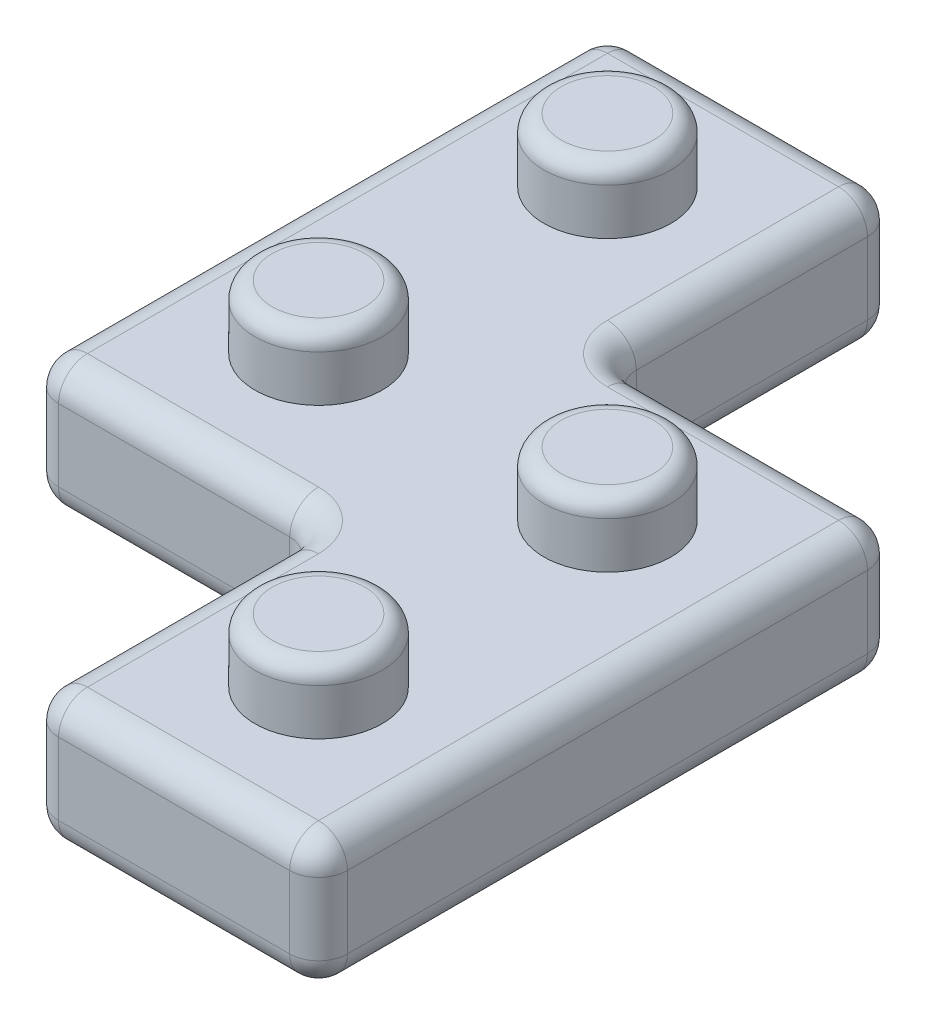
SolidWorks part; units mm, degrees
ref_plane "Front Plane" through (0, 0, 0) normal (0, 0, 1) x (1, 0, 0)
ref_plane "Top Plane" through (0, 0, 0) normal (0, 1, 0) x (1, 0, 0)
ref_plane "Right Plane" through (0, 0, 0) normal (1, 0, 0) x (0, 0, -1)
sketch "Sketch1" plane through (0, 0, 0) normal (0, 1, 0) x (1, 0, 0)
  line L0 (-11.43, 12.7) -> (-1.27, 12.7)
  line L1 (0, 11.43) -> (0, 1.27)
  line L2 (1.27, 0) -> (11.43, 0)
  line L3 (12.7, -1.27) -> (12.7, -24.13)
  line L4 (11.43, -25.4) -> (1.27, -25.4)
  line L5 (0, -24.13) -> (0, -13.97)
  line L6 (-1.27, -12.7) -> (-11.43, -12.7)
  line L7 (-12.7, -11.43) -> (-12.7, 11.43)
  arc A4 (-11.43, 12.7) -> (-12.7, 11.43) centre (-11.43, 11.43) ccw
  arc A5 (-11.43, -12.7) -> (-12.7, -11.43) centre (-11.43, -11.43) cw
  arc A6 (0, -13.97) -> (-1.27, -12.7) centre (-1.27, -13.97) ccw
  arc A7 (1.27, -25.4) -> (0, -24.13) centre (1.27, -24.13) cw
  arc A8 (12.7, -24.13) -> (11.43, -25.4) centre (11.43, -24.13) cw
  arc A9 (0, 1.27) -> (1.27, 0) centre (1.27, 1.27) ccw
  arc A10 (11.43, 0) -> (12.7, -1.27) centre (11.43, -1.27) cw
  arc A11 (-1.27, 12.7) -> (0, 11.43) centre (-1.27, 11.43) cw
  point P11 (-12.7, 12.7)
  point P14 (-12.7, -12.7)
  point P17 (0, 0)
  point P18 (0, 0)
  point P19 (0, 0)
  point P22 (0, -25.4)
  point P25 (12.7, -25.4)
  point P28 (0, 0)
  point P31 (12.7, 0)
  point P34 (0, 12.7)
  dimension "D6" = 1.27
  dimension "D1" = 12.7
  dimension "D2" = 12.7
  dimension "D3" = 25.4
  dimension "D4" = 12.7
  dimension "D5" = 25.4
extrude "Boss-Extrude1" add sketch "Sketch1" against normal blind 5.715 contours L7 A4 L0 A11 L1 A9 L2 A10 L3 A8 L4 A7 L5 A6 L6 A5
sketch "Sketch2" plane through (0, 0, 0) normal (0, 1, 0) x (1, 0, 0)
  line L0 (-11.43, 12.7) -> (-1.27, 12.7) construction
  line L1 (-12.7, -11.43) -> (-12.7, 11.43) construction
  circle A0 centre (-6.35, 6.35) radius 2.794
  circle A1 centre (-6.35, -6.35) radius 2.794
  circle A2 centre (6.35, -6.35) radius 2.794
  circle A3 centre (6.35, -19.05) radius 2.794
  point P8 (0, 0)
  point P9 (0, 0)
  point P10 (0, 0)
  dimension "D1" = 12.7
  dimension "D2" = 6.35
  dimension "D3" = 6.35
  dimension "D4" = 12.7
  dimension "D5" = 12.7
extrude "Boss-Extrude2" add sketch "Sketch2" along normal blind 2.794
fillet "Fillet4" radius 1.27 16 edges at (-6.35, 0, 12.7) (0, 0, 19.05) (6.35, 0, 25.4) (12.7, 0, 12.7) (6.35, 0, 0) (0, 0, -6.35) (-6.35, 0, -12.7) (-12.7, 0, 0) (-12.328, 0, 12.328) (-0.372, 0, 13.072) (0.372, 0, 25.028) (12.328, 0, 25.028) (12.328, 0, 0.372) (0.372, 0, -0.372) (-0.372, 0, -12.328) (-12.328, 0, -12.328)
fillet "Fillet5" radius 1.27 16 edges at (0, -5.715, -6.35) (6.35, -5.715, 0) (12.7, -5.715, 12.7) (6.35, -5.715, 25.4) (0, -5.715, 19.05) (-6.35, -5.715, 12.7) (-12.7, -5.715, 0) (-6.35, -5.715, -12.7) (-12.328, -5.715, -12.328) (-12.328, -5.715, 12.328) (-0.372, -5.715, 13.072) (0.372, -5.715, 25.028) (12.328, -5.715, 25.028) (12.328, -5.715, 0.372) (0.372, -5.715, -0.372) (-0.372, -5.715, -12.328)
fillet "Fillet7" radius 0.762 4 edges at (6.35, 2.794, 21.844) (6.35, 2.794, 9.144) (-6.35, 2.794, 9.144) (-6.35, 2.794, -3.556)
